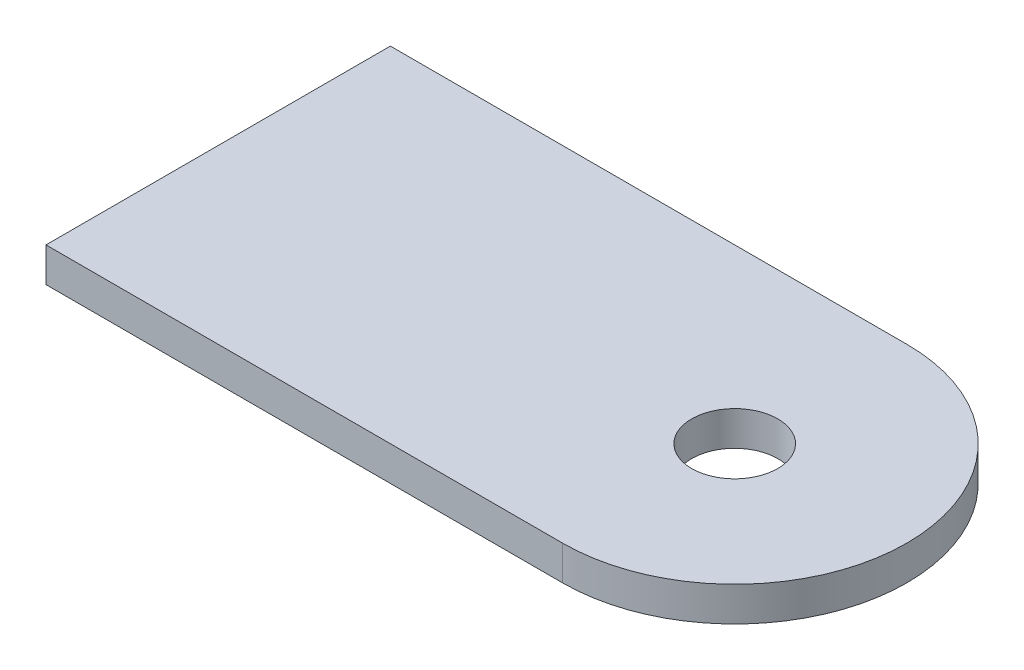
SolidWorks part; units mm, degrees
ref_plane "Front Plane" through (0, 0, 0) normal (0, 0, 1) x (1, 0, 0)
ref_plane "Top Plane" through (0, 0, 0) normal (0, 1, 0) x (1, 0, 0)
ref_plane "Right Plane" through (0, 0, 0) normal (1, 0, 0) x (0, 0, -1)
sketch "Sketch1" plane through (0, 0, 0) normal (0, 1, 0) x (1, 0, 0)
  line L0 (60, 40) -> (60, 0) construction
  line L1 (0, 0) -> (40, 0)
  line L2 (0, 0) -> (0, 40)
  line L3 (0, 40) -> (40, 40)
  line L4 (40, 0) -> (40, 40)
  line L5 (40, 40) -> (60, 40)
  line L6 (40, 40) -> (40, 0)
  line L7 (40, 0) -> (60, 0)
  line L9 (80, 20) -> (40, 20) construction
  circle A0 centre (60, 20) radius 5
  arc A1 (60, 40) -> (60, 0) centre (60, 20) cw
  dimension "D4" = 10
  dimension "D1" = 40
  dimension "D2" = 40
extrude "Boss-Extrude1" add sketch "Sketch1" along normal blind 4 contours A1 L5 L4 L7 A0 | L1 L4 L3 L2
